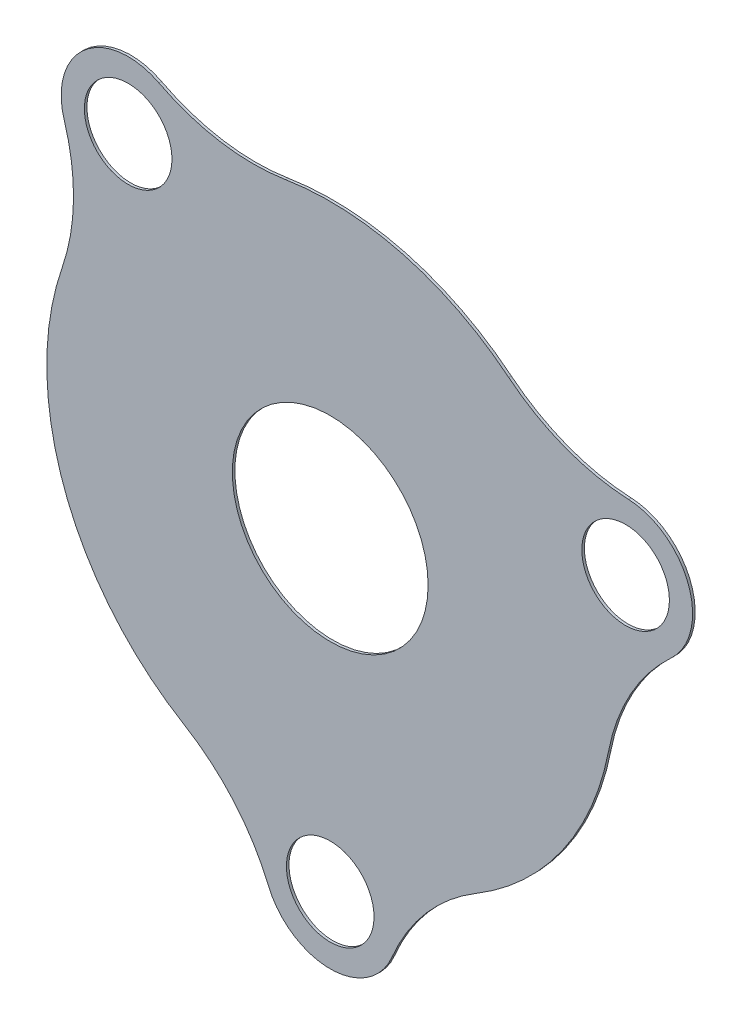
SolidWorks part; units mm, degrees
material "TESNIT BA-GL"
ref_plane "Front Plane" through (0, 0, 0) normal (0, 0, 1) x (1, 0, 0)
ref_plane "Top Plane" through (0, 0, 0) normal (0, 1, 0) x (1, 0, 0)
ref_plane "Right Plane" through (0, 0, 0) normal (1, 0, 0) x (0, 0, -1)
sketch "Sketch1" plane through (0, 0, 0) normal (0, 0, 1) x (1, 0, 0)
  line L0 (-39.21, 46.7287) -> (0, -61) construction
  line L1 (0, 0) -> (57.3212, 20.8632) construction
  line L2 (0, 0) -> (-39.21, 46.7287) construction
  line L3 (-39.21, 46.7287) -> (0, 0) construction
  line L4 (0, 0) -> (0, -61) construction
  arc A12 (-11.9932, -66.0162) -> (11.9932, -66.0162) centre (0, -61) ccw
  arc A13 (-33.2471, 58.2805) -> (-51.6218, 42.8623) centre (-39.21, 46.7287) ccw
  arc A14 (66.1369, 11.3089) -> (57.933, 33.8488) centre (57.3212, 20.8632) ccw
  arc A15 (-51.9962, 17.9274) -> (-51.6218, 42.8623) centre (-89.8117, 30.9656) ccw
  arc A16 (-33.2471, 58.2805) -> (-8.626, 54.3193) centre (-14.8995, 93.8243) ccw
  arc A17 (34.63, 42.7289) -> (-8.626, 54.3193) centre (0, 0) ccw
  arc A18 (34.63, 42.7289) -> (57.933, 33.8488) centre (59.8155, 73.8045) ccw
  arc A19 (66.1369, 11.3089) -> (53.9938, -10.4725) centre (93.262, -18.0889) ccw
  arc A20 (28.3079, -47.1557) -> (53.9938, -10.4725) centre (0, 0) ccw
  arc A21 (28.3079, -47.1557) -> (11.9932, -66.0162) centre (48.8954, -81.4508) ccw
  arc A22 (-11.9932, -66.0162) -> (-28.3079, -47.1557) centre (-48.8954, -81.4508) ccw
  arc A23 (-51.9962, 17.9274) -> (-28.3079, -47.1557) centre (0, 0) ccw
  circle A24 centre (57.3212, 20.8632) radius 8.5
  circle A25 centre (-39.21, 46.7287) radius 8.5
  circle A26 centre (0, -61) radius 8.5
  circle A27 centre (0, 0) radius 19
  circle A28 centre (0, 0) radius 61 construction
  dimension "D1" = 17
  dimension "D2" = 38
  dimension "D3" = 122
  dimension "D4" = 13
  dimension "D5" = 55
  dimension "D8" = 40
  dimension "D6" = 110
  dimension "D7" = 110
extrude "Extrude1" add sketch "Sketch1" along normal blind 0.5
